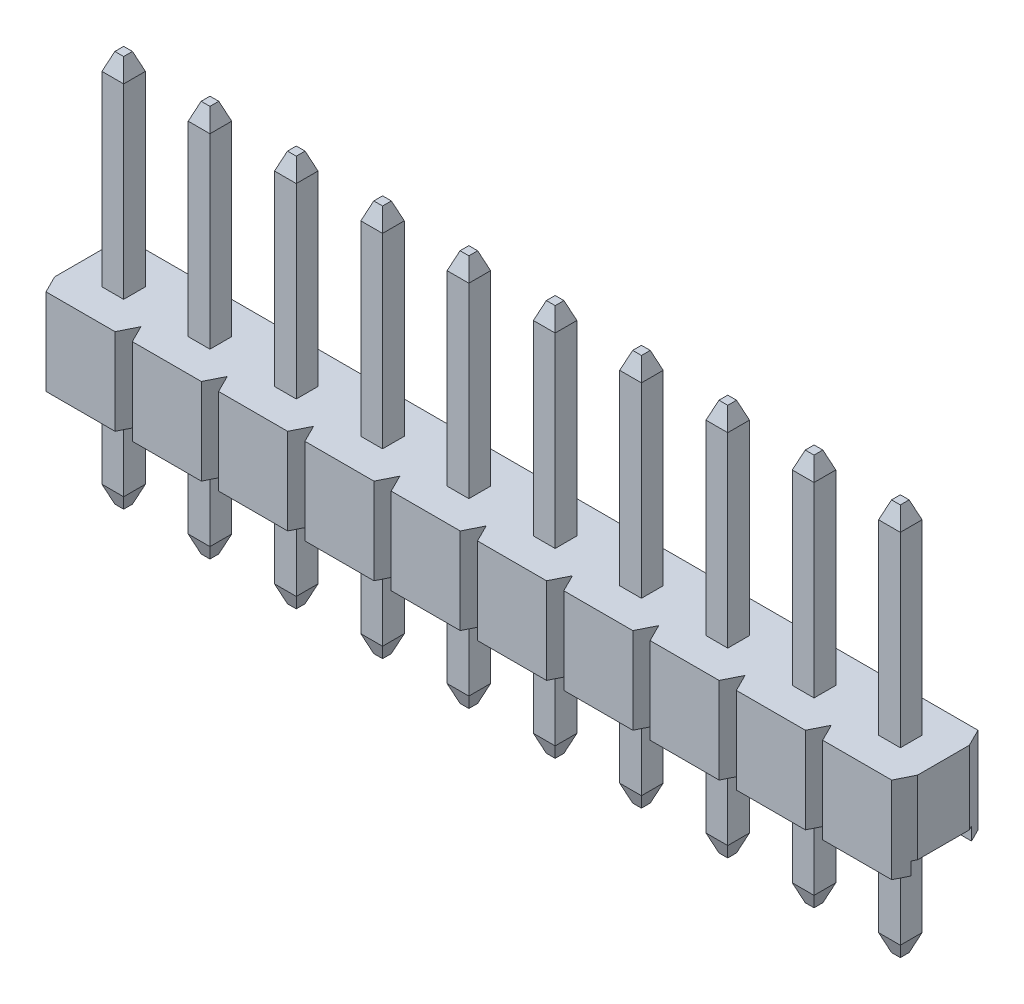
SolidWorks part; units mm, degrees
ref_plane "Front Plane" through (0, 0, 0) normal (0, 0, 1) x (1, 0, 0)
ref_plane "Top Plane" through (0, 0, 0) normal (0, 1, 0) x (1, 0, 0)
ref_plane "Right Plane" through (0, 0, 0) normal (1, 0, 0) x (0, 0, -1)
sketch "Sketch1" plane through (0, 0, 0) normal (0, 1, 0) x (1, 0, 0)
  line L1 (0, 0) -> (2.54, 0)
  line L2 (0, 0) -> (0, 2.54)
  line L3 (0, 2.54) -> (2.54, 2.54)
  line L4 (2.54, 0) -> (2.54, 2.54)
  dimension "D1" = 2.54
  dimension "D2" = 2.54
extrude "Main Body" add sketch "Sketch1" along normal blind 2.54
sketch "Sketch3" plane through (0, 0, 0) normal (-1, 0, 0) x (0, 0, 1)
  line L0 (-2.54, 0) -> (0, 0) construction
  line L1 (-2.159, 0) -> (-0.381, 0)
  line L2 (-2.159, 0) -> (-2.159, 0.381)
  line L3 (-2.159, 0.381) -> (-0.381, 0.381)
  line L4 (-0.381, 0) -> (-0.381, 0.381)
  line L5 (-2.54, 0) -> (-2.159, 0) construction
  line L6 (-0.381, 0) -> (0, 0) construction
  dimension "D1" = 0.381
extrude "Cut-Extrude1" cut sketch "Sketch3" against normal through all
sketch "Sketch4" plane through (0, 2.54, 0) normal (0, 1, 0) x (1, 0, 0)
  line L0 (0, 2.54) -> (0, 2.032)
  line L1 (0, 2.54) -> (0, 0) construction
  line L2 (0, 2.032) -> (0.254, 2.54)
  line L3 (2.54, 2.54) -> (0, 2.54) construction
  line L4 (0.254, 2.54) -> (0, 2.54)
  line L5 (2.54, 2.54) -> (2.286, 2.54)
  line L6 (2.286, 2.54) -> (2.54, 2.032)
  line L7 (2.54, 0) -> (2.54, 2.54) construction
  line L8 (2.54, 2.032) -> (2.54, 2.54)
  line L9 (2.54, 0) -> (2.286, 0)
  line L10 (0, 0) -> (2.54, 0) construction
  line L11 (2.286, 0) -> (2.54, 0.508)
  line L12 (2.54, 0.508) -> (2.54, 0)
  line L14 (0, 0) -> (0, 0.508)
  line L15 (0, 0.508) -> (0.254, 0)
  line L16 (0.254, 0) -> (0, 0)
  line M1 (0, 2.54) -> (0, 0)
  line M2 (0, 0) -> (2.54, 0)
  line M3 (2.54, 0) -> (2.54, 2.54)
  line M4 (2.54, 2.54) -> (0, 2.54)
  dimension "D1" = 0.254
  dimension "D2" = 0.508
extrude "Cut-Extrude2" cut sketch "Sketch4" against normal through all contours L2 M1 M4 | L6 M4 M3 | L15 M1 M2 | L9 L11 L12
pattern_linear "Body Pattern" count 10 spacing 2.54 along (-1, 0, 0) of "Main Body", "Cut-Extrude1", "Cut-Extrude2"
sketch "Sketch2" plane through (0, 2.54, 0) normal (0, 1, 0) x (1, 0, 0)
  line L0 (1.27, 2.54) -> (1.27, 1.59) construction
  line L1 (0.95, 0.95) -> (1.59, 0.95)
  line L2 (0.95, 0.95) -> (0.95, 1.59)
  line L3 (0.95, 1.59) -> (1.59, 1.59)
  line L4 (1.59, 0.95) -> (1.59, 1.59)
  line L6 (2.286, 2.54) -> (0.254, 2.54) construction
  line L8 (1.27, 0.95) -> (1.27, 0) construction
  line L9 (0.254, 0) -> (2.286, 0) construction
  dimension "D1" = 0.64
extrude "Pin" add sketch "Sketch2" along normal blind 6 and the other way offset from surface (5.54 mm away) 3 other way up to face at (1.27, 0, -0.1905)
chamfer "Chamfer1" distance 0.508 distance2 0.1905 4 edges at (0.95, 8.54, -1.27) (1.27, 8.54, -1.59) (1.59, 8.54, -1.27) (1.27, 8.54, -0.95)
chamfer "Chamfer2" distance 0.1905 distance2 0.508 4 edges at (1.27, -3, -1.59) (1.59, -3, -1.27) (1.27, -3, -0.95) (0.95, -3, -1.27)
pattern_linear "Pin Pattern" count 10 spacing 2.54 along (-1, 0, 0) of "Pin", "Chamfer1", "Chamfer2"
pattern_linear "Row Pattern" [suppressed] count 2 spacing 2.54
